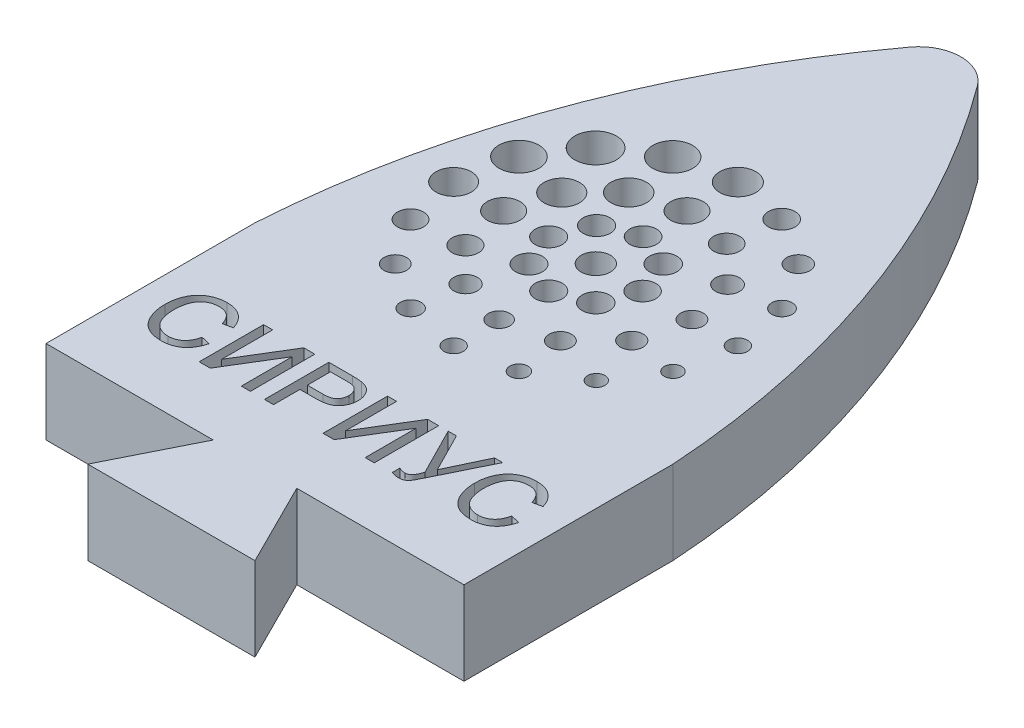
SolidWorks part; units mm, degrees
ref_plane "Спереди" through (0, 0, 0) normal (0, 0, 1) x (1, 0, 0)
ref_plane "Сверху" through (0, 0, 0) normal (0, 1, 0) x (1, 0, 0)
ref_plane "Справа" through (0, 0, 0) normal (1, 0, 0) x (0, 0, -1)
sketch "Эскиз1" plane through (0, 0, 0) normal (0, 1, 0) x (1, 0, 0)
  line L0 (0, 0) -> (0, -21.5) construction
  line L1 (10, -17.5) -> (2, -17.5)
  line L2 (10, -17.5) -> (10, -7.5)
  line L4 (-10, -17.5) -> (-10, -7.5)
  line L5 (-4, -21.5) -> (4, -21.5)
  line L6 (4, -21.5) -> (2, -17.5)
  line L7 (-4, -21.5) -> (-2, -17.5)
  line L8 (-2, -17.5) -> (-10, -17.5)
  arc A0 (-1.6075, 15.4595) -> (-10, -7.5) centre (33.1259, -10.2503) ccw
  arc A1 (1.6075, 15.4595) -> (10, -7.5) centre (-33.1259, -10.2503) cw
  arc A2 (1.6075, 15.4595) -> (-1.6075, 15.4595) centre (0, 14.2696) ccw
  point P0 (0, 0)
  point P6 (-10, -7.5)
  point P14 (0, 17.5)
  dimension "D1" = 2
  dimension "D2" = 20
  dimension "D3" = 10
  dimension "D4" = 8
  dimension "D5" = 4
  dimension "D6" = 4
extrude "Бобышка-Вытянуть1" add sketch "Эскиз1" along normal blind 4 contours A0 L4 L8 L7 L5 L6 L1 L2 A1 A2
sketch "Эскиз2" plane through (0, 0, 0) normal (0, 1, 0) x (1, 0, 0)
  line L3 (-0.1372, -0.3715) -> (-0.1372, -1.7212) construction
  circle A46 centre (-2.7382, 5.2253) radius 0.9553
  circle A47 centre (-4.9538, 3.7518) radius 0.9952
  circle A48 centre (-6.425, 1.5554) radius 0.9597
  circle A49 centre (-6.9424, -1.0519) radius 0.845
  circle A50 centre (-6.4175, -3.6416) radius 0.6237
  circle A51 centre (-4.9405, -5.8471) radius 0.5389
  circle A52 centre (-2.7322, -7.3162) radius 0.4988
  circle A53 centre (-0.1484, -7.8439) radius 0.4636
  circle A54 centre (2.466, -7.3377) radius 0.432
  circle A55 centre (4.6992, -5.8681) radius 0.4125
  circle A56 centre (6.1586, -3.657) radius 0.4157
  circle A57 centre (-0.1351, 5.7407) radius 0.8652
  circle A58 centre (-0.1553, 3.3269) radius 0.7786
  circle A59 centre (-0.1385, 1.2102) radius 0.6391
  circle A60 centre (-2.3148, 2.6992) radius 0.8533
  circle A61 centre (-3.9116, 1.0905) radius 0.8494
  circle A62 centre (-4.5451, -1.0567) radius 0.7806
  circle A63 centre (-4.0359, -3.3946) radius 0.6283
  circle A64 centre (-2.4218, -5.0025) radius 0.5657
  circle A65 centre (-0.1455, -5.6712) radius 0.5178
  circle A66 centre (2.193, -5.0799) radius 0.5394
  circle A67 centre (3.8952, -3.3668) radius 0.5462
  circle A68 centre (6.161, 1.5565) radius 0.4864
  circle A69 centre (4.7097, 3.7881) radius 0.5512
  circle A70 centre (2.4535, 5.2508) radius 0.6386
  circle A71 centre (2.1522, 2.9184) radius 0.6216
  circle A72 centre (3.8661, 1.247) radius 0.5717
  circle A73 centre (1.4737, 0.5609) radius 0.6536
  circle A74 centre (-1.7134, 0.5587) radius 0.647
  circle A75 centre (-2.3912, -1.0559) radius 0.6451
  circle A76 centre (2.1018, -1.0542) radius 0.6354
  circle A77 centre (-0.153, -1.0386) radius 0.6991
  circle A78 centre (-1.7343, -2.6541) radius 0.6439
  circle A79 centre (-0.1471, -3.2974) radius 0.6463
  circle A80 centre (1.4684, -2.6608) radius 0.6513
  circle A81 centre (4.4635, -1.0539) radius 0.539
  circle A82 centre (6.6506, -1.0439) radius 0.4649
  text T0 "https://vk.com/siriusdeti" font "Arial" height in points 8
  point P142 (0, 0)
extrude "Вырез-Вытянуть4" cut sketch "Эскиз2" against normal blind 5 and the other way through all
sketch "Эскиз3" plane through (0, 0, 0) normal (0, 1, 0) x (1, 0, 0)
  text T0 "СИРИУС" font "Arial" height in points 12
  point P1 (-9.2141, -16.1158)
  point P2 (0, 0)
  point P3 (0, 0)
  point P4 (-9.0538, -12.6705)
  point P5 (0, 0)
  point P6 (0, 0)
  point P7 (-8.9737, -14.5935)
extrude "Вырез-Вытянуть7" cut sketch "Эскиз3" along normal through all
